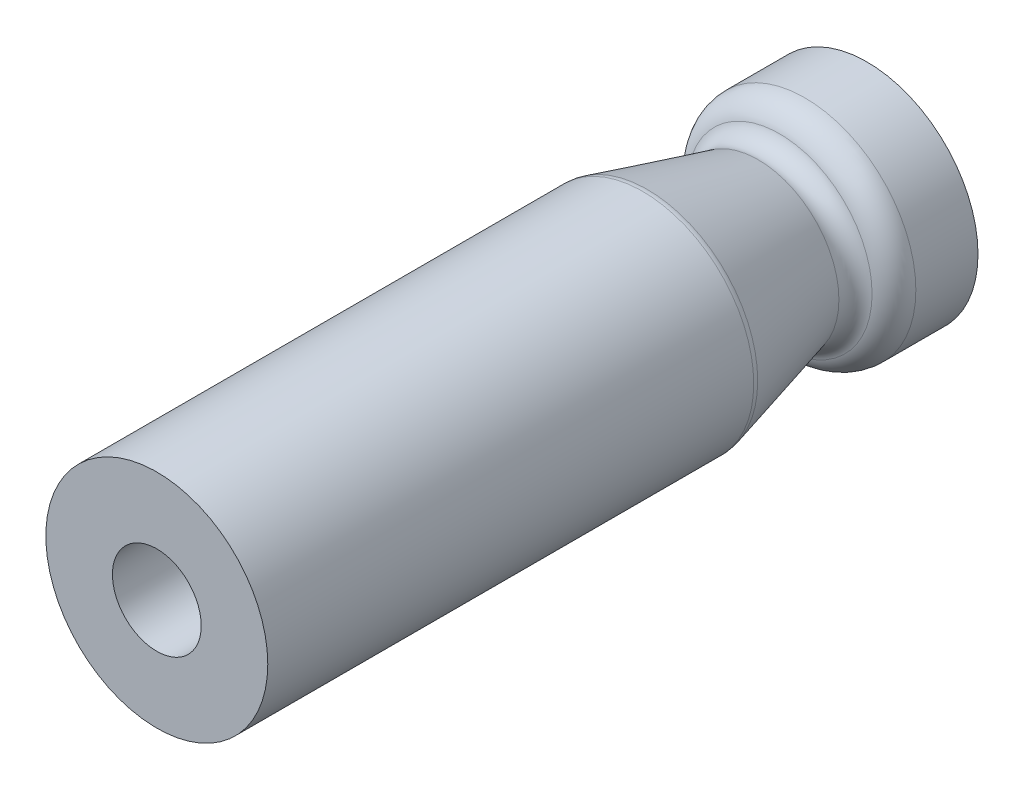
SolidWorks part; units mm, degrees
ref_plane "Спереди" through (0, 0, 0) normal (0, 0, 1) x (1, 0, 0)
ref_plane "Сверху" through (0, 0, 0) normal (0, 1, 0) x (1, 0, 0)
ref_plane "Справа" through (0, 0, 0) normal (1, 0, 0) x (0, 0, -1)
sketch "Эскиз1" plane through (0, 0, 0) normal (0, 0, 1) x (1, 0, 0)
  circle A0 centre (0, 0) radius 5
  dimension "D1" = 10
extrude "Вытянуть-Тонкостенный1" add sketch "Эскиз1" along normal blind 80 thin
sketch "Эскиз2" plane through (0, 0, 0) normal (0, 1, 0) x (1, 0, 0)
  line L0 (12.5, -10) -> (8.5, -10)
  line L1 (12.5, -80) -> (12.5, 0) construction
  line L2 (8.5, -10) -> (12.5, -25)
  line L3 (12.5, -25) -> (12.5, -10)
  line L4 (0, 6.5996) -> (0, -41.9388) construction
  dimension "D1" = 4
  dimension "D2" = 10
  dimension "D3" = 15
revolve "Вырез-Повернуть1" cut sketch "Эскиз2" angle 360 about L4
fillet "Скругление1" radius 3 1 edges at (-12.5, 0, 10)
fillet "Скругление2" radius 2 1 edges at (-8.5, 0, 10)
fillet "Скругление3" radius 2 1 edges at (-12.5, 0, 25)
